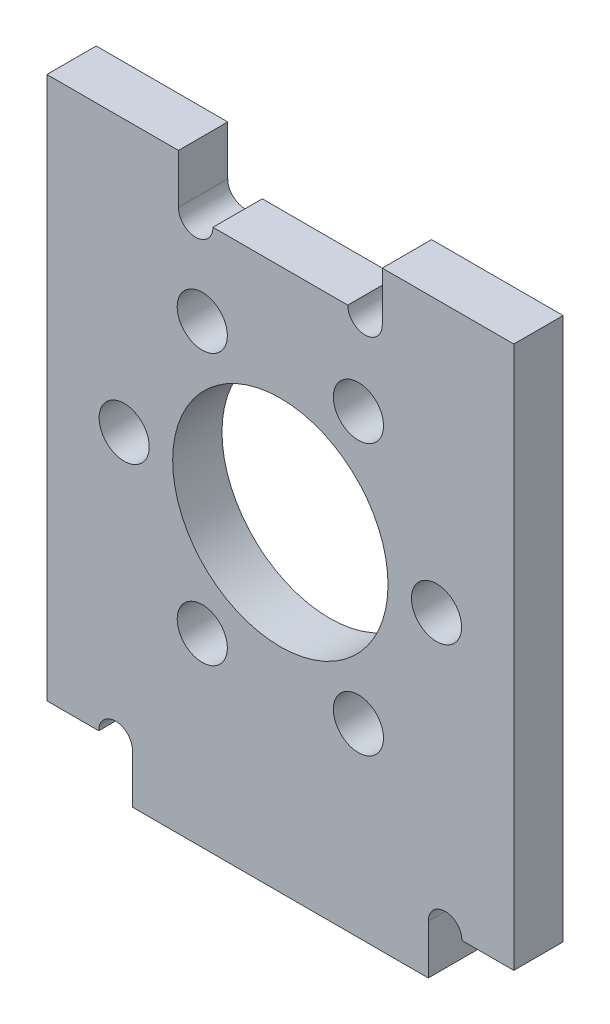
SolidWorks part; units mm, degrees
material "Thornel Mat VMA"
ref_plane "前视基准面" through (0, 0, 0) normal (0, 0, 1) x (1, 0, 0)
ref_plane "上视基准面" through (0, 0, 0) normal (0, 1, 0) x (1, 0, 0)
ref_plane "右视基准面" through (0, 0, 0) normal (1, 0, 0) x (0, 0, -1)
other "Configuration Table"
sketch "草图1" plane through (0, 0, 0) normal (0, 0, 1) x (1, 0, 0)
  line L1 (-14.2, -15) -> (14.2, -15)
  line L2 (-14.2, -15) -> (-14.2, 15)
  line L3 (-14.2, 15) -> (14.2, 15)
  line L4 (14.2, -15) -> (14.2, 15)
  line L5 (-14.2, -15) -> (14.2, 15) construction
  line L6 (-14.2, 15) -> (14.2, -15) construction
  point P0 (0, 0)
  dimension "D1" = 28.4
  dimension "D2" = 30
extrude "凸台-拉伸1" add sketch "草图1" along normal blind 3
sketch "草图2" plane through (0, 0, 3) normal (0, 0, 1) x (1, 0, 0)
  circle A0 centre (0, 1.5) radius 6.5 construction
  circle A1 centre (0, 1.5) radius 6.5 construction
  circle A2 centre (0, 1.5) radius 6.55
  dimension "D1" = 0.05
extrude "切除-拉伸1" cut sketch "草图2" against normal blind 3
sketch "草图3" plane through (0, 0, 3) normal (0, 0, 1) x (1, 0, 0)
  circle A0 centre (-9.5, 1.5) radius 1.25 construction
  circle A1 centre (-9.5, 1.5) radius 1.25 construction
  circle A2 centre (-9.5, 1.5) radius 1.525
  dimension "D1" = 3.05
extrude "切除-拉伸2" cut sketch "草图3" against normal blind 3
pattern_circular "阵列(圆周)1" count 6 over 360 about axis through (0, 1.5, 0) along (0, 0, 1) of "切除-拉伸2"
sketch "草图4" plane through (0, 0, 0) normal (0, 0, -1) x (-1, 0, 0)
  line L1 (-14.2, 15) -> (-6.2, 15)
  line L2 (-14.2, 15) -> (-14.2, 18)
  line L3 (-14.2, 18) -> (-6.2, 18)
  line L4 (-6.2, 15) -> (-6.2, 18)
  line L5 (14.2, 15) -> (6.2, 15)
  line L6 (14.2, 15) -> (14.2, 18)
  line L7 (14.2, 18) -> (6.2, 18)
  line L8 (6.2, 15) -> (6.2, 18)
  dimension "D1" = 3
  dimension "D2" = 8
extrude "凸台-拉伸2" add sketch "草图4" against normal up to surface (3 mm away) up to face at (-3.9875, 8.4066, 3)
sketch "草图5" plane through (0, 0, 3) normal (0, 0, 1) x (1, 0, 0)
  line L0 (6.2, 15) -> (-6.2, 15) construction
  circle A0 centre (-5.15, 15) radius 1.05
  circle A1 centre (5.15, 15) radius 1.05
  dimension "D1" = 2.1
extrude "切除-拉伸3" cut sketch "草图5" against normal up to surface (3 mm away) up to face at (-3.9875, 8.4066, 0)
sketch "草图6" plane through (0, 0, 0) normal (0, 0, -1) x (-1, 0, 0)
  line L0 (14.2, -15) -> (-14.2, -15) construction
  line L1 (-9, -18) -> (9, -18)
  line L2 (-9, -18) -> (-9, -12)
  line L3 (-9, -12) -> (9, -12)
  line L4 (9, -18) -> (9, -12)
  line L5 (-9, -18) -> (9, -12) construction
  line L6 (-9, -12) -> (9, -18) construction
  point P0 (0, -15)
  dimension "D1" = 3
  dimension "D2" = 18
extrude "凸台-拉伸3" add sketch "草图6" against normal up to surface (3 mm away) up to face at (-3.9875, 8.4066, 3)
sketch "草图7" plane through (0, 0, 0) normal (0, 0, -1) x (-1, 0, 0)
  line L1 (14.2, -15) -> (9, -15) construction
  line L2 (-9, -15) -> (-14.2, -15) construction
  circle A1 centre (10.025, -15) radius 1.025
  circle A2 centre (-10.025, -15) radius 1.025
  dimension "D1" = 2.05
extrude "切除-拉伸4" cut sketch "草图7" against normal up to surface (3 mm away) up to face at (0, 2.4214, 3)
